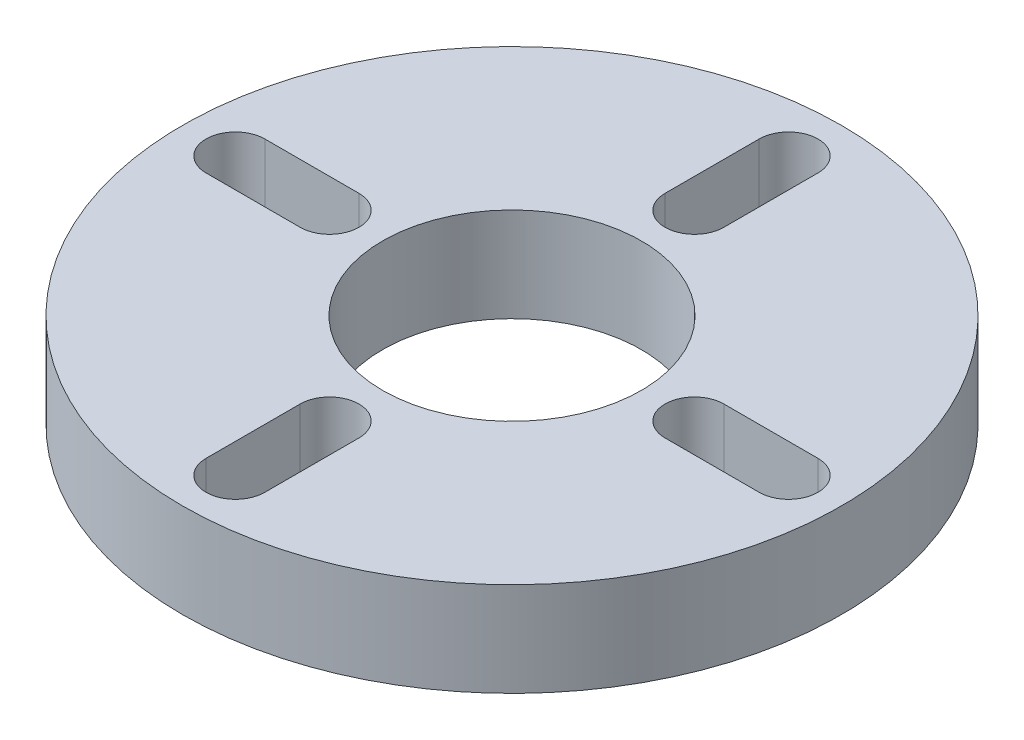
SolidWorks part; units mm, degrees
ref_plane "Front Plane" through (0, 0, 0) normal (0, 0, 1) x (1, 0, 0)
ref_plane "Top Plane" through (0, 0, 0) normal (0, 1, 0) x (1, 0, 0)
ref_plane "Right Plane" through (0, 0, 0) normal (1, 0, 0) x (0, 0, -1)
sketch "Sketch1" plane through (0, 0, 0) normal (0, 1, 0) x (1, 0, 0)
  circle A0 centre (0, 0) radius 14
  circle A1 centre (0, 0) radius 5.5
  dimension "D1" = 28
  dimension "D2" = 11
extrude "Boss-Extrude1" add sketch "Sketch1" along normal blind 4 contours A0
sketch "Sketch2" plane through (0, 4, 0) normal (0, 1, 0) x (1, 0, 0)
  circle A0 centre (0, 0) radius 5.5
  dimension "D1" = 11
extrude "Cut-Extrude1" cut sketch "Sketch2" against normal through all
sketch "Sketch3" plane through (0, 4, 0) normal (0, 1, 0) x (1, 0, 0)
  line L0 (-11.75, 0) -> (-7.75, 0) construction
  line L1 (-14, 0) -> (-5.5, 0) construction
  line L2 (-11.75, 1.25) -> (-7.75, 1.25)
  line L3 (-11.75, -1.25) -> (-7.75, -1.25)
  line L4 (-1.25, 11.75) -> (-1.25, 7.75)
  line L5 (1.25, 11.75) -> (1.25, 7.75)
  line L6 (0, 11.75) -> (0, 7.75) construction
  line L7 (11.75, 1.25) -> (7.75, 1.25)
  line L8 (11.75, -1.25) -> (7.75, -1.25)
  line L9 (11.75, 0) -> (7.75, 0) construction
  line L10 (1.25, -11.75) -> (1.25, -7.75)
  line L11 (-1.25, -11.75) -> (-1.25, -7.75)
  line L12 (0, -11.75) -> (0, -7.75) construction
  circle A0 centre (0, 0) radius 14 construction
  circle A1 centre (0, 0) radius 5.5 construction
  arc A2 (-11.75, 1.25) -> (-11.75, -1.25) centre (-11.75, 0) ccw
  arc A3 (-7.75, -1.25) -> (-7.75, 1.25) centre (-7.75, 0) ccw
  arc A4 (1.25, 11.75) -> (-1.25, 11.75) centre (0, 11.75) ccw
  arc A5 (-1.25, 7.75) -> (1.25, 7.75) centre (0, 7.75) ccw
  arc A6 (11.75, -1.25) -> (11.75, 1.25) centre (11.75, 0) ccw
  arc A7 (7.75, 1.25) -> (7.75, -1.25) centre (7.75, 0) ccw
  arc A8 (-1.25, -11.75) -> (1.25, -11.75) centre (0, -11.75) ccw
  arc A9 (1.25, -7.75) -> (-1.25, -7.75) centre (0, -7.75) ccw
  point P5 (0, 0)
  point P12 (-9.75, 0)
  point P20 (0, 9.75)
  point P27 (9.75, 0)
  point P34 (0, -9.75)
  point P39 (0, 0)
  dimension "D1" = 4
extrude "Cut-Extrude3" cut sketch "Sketch3" against normal through all
